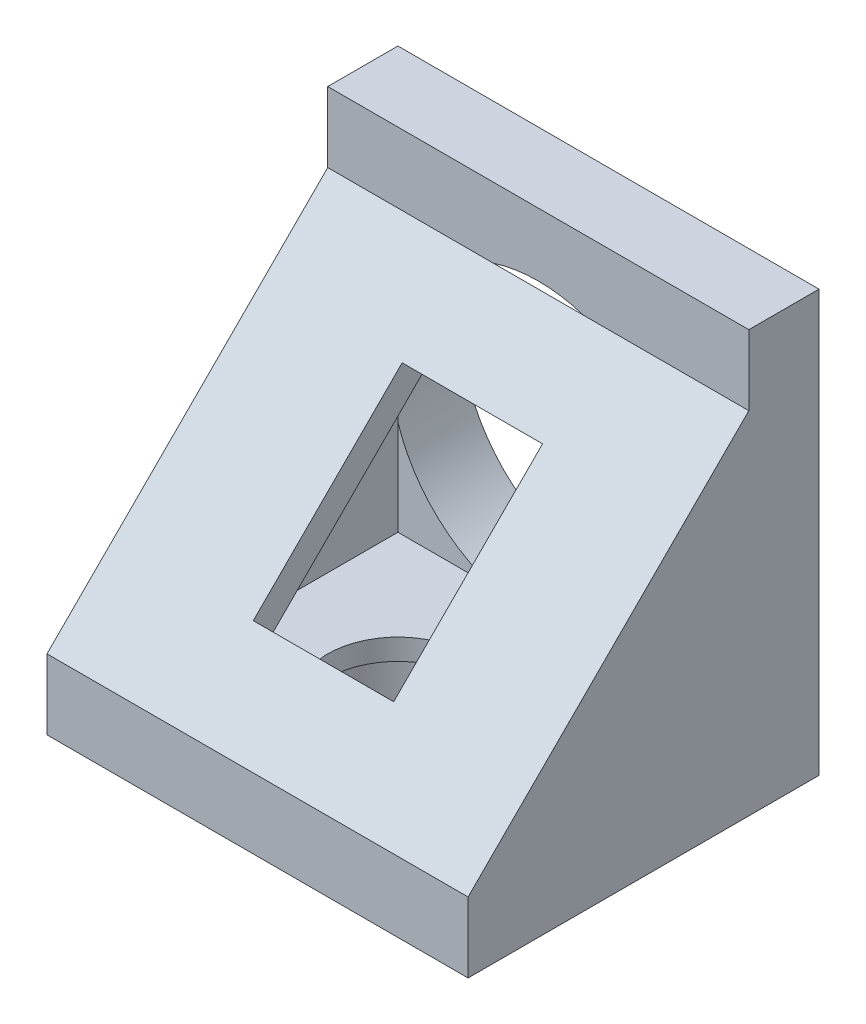
SolidWorks part; units mm, degrees
ref_plane "Front Plane" through (0, 0, 0) normal (1, 0, 0) x (0, 1, 0)
ref_plane "Top Plane" through (0, 0, 0) normal (0, 0, 1) x (0, 1, 0)
ref_plane "Right Plane" through (0, 0, 0) normal (0, 1, 0) x (-1, 0, 0)
sketch "Sketch1" plane through (0, 0, 0) normal (0, 0, 1) x (0, 1, 0)
  line L1 (-15, -15) -> (15, -15)
  line L2 (-15, -15) -> (-15, 15)
  line L3 (-15, 15) -> (15, 15)
  line L4 (15, -15) -> (15, 15)
  line L5 (-15, -15) -> (15, 15) construction
  line L6 (-15, 15) -> (15, -15) construction
  point P0 (0, 0)
  dimension "D1" = 30
  dimension "D2" = 30
extrude "Boss-Extrude1" add sketch "Sketch1" along normal blind 25
sketch "Sketch2" plane through (0, 0, 25) normal (0, 0, 1) x (1, 0, 0)
  line L1 (-10, -10) -> (10, -10)
  line L2 (-10, -10) -> (-10, 10)
  line L3 (-10, 10) -> (10, 10)
  line L4 (10, -10) -> (10, 10)
  line L5 (-10, -10) -> (10, 10) construction
  line L6 (-10, 10) -> (10, -10) construction
  point P0 (0, 0)
  dimension "D1" = 20
  dimension "D2" = 20
extrude "Cut-Extrude1" cut sketch "Sketch2" against normal blind 20
sketch "Sketch3" plane through (15, 0, 0) normal (1, 0, 0) x (0, 1, 0)
  line L0 (-15, 30) -> (15, 0)
  line L1 (15, 0) -> (-15, 0)
  line L2 (15, 0) -> (15, 30)
  line L3 (15, 30) -> (-15, 30)
  line L4 (-15, 0) -> (-15, 30)
  line L5 (-15, 0) -> (-15, 5)
  line L7 (-15, 5) -> (15, 5)
  line L8 (-15, 5) -> (-15, 0)
  line L9 (-15, 0) -> (15, 0)
  line L10 (15, 5) -> (15, 0)
  line M7 (15, 25) -> (-15, 25)
  dimension "D1" = 30
  dimension "D2" = 30
  dimension "D3" = 5
extrude "Cut-Extrude2" cut sketch "Sketch3" against normal blind 43 contours L0 L7 L2 M7
sketch "Sketch4" plane through (0, 7.5, 7.5) normal (0, 0.7071, 0.7071) x (-1, 0, 0)
  line L0 (10, 10.6066) -> (-10, 10.6066) construction
  line L1 (-15, 24.7487) -> (15, 24.7487)
  line L2 (-15, 24.7487) -> (-15, -3.5355)
  line L3 (-15, -3.5355) -> (15, -3.5355)
  line L4 (15, 24.7487) -> (15, -3.5355)
  line L5 (-5, 3.1066) -> (5, 3.1066)
  line L6 (-5, 3.1066) -> (-5, 18.1066)
  line L7 (-5, 18.1066) -> (5, 18.1066)
  line L8 (5, 3.1066) -> (5, 18.1066)
  line L9 (-5, 3.1066) -> (5, 18.1066) construction
  line L10 (-5, 18.1066) -> (5, 3.1066) construction
  point P6 (0, 10.6066)
  dimension "D1" = 10
  dimension "D2" = 15
extrude "Boss-Extrude2" add sketch "Sketch4" against normal blind 2
sketch "Sketch5" plane through (0, 0, 0) normal (0, 0, -1) x (1, 0, 0)
  circle A0 centre (0, 0) radius 10.5
extrude "Cut-Extrude4" cut sketch "Sketch5" against normal blind 5
sketch "Sketch6" plane through (0, -15, 0) normal (0, -1, 0) x (1, 0, 0)
  line L0 (15, 25) -> (15, 0) construction
  line L1 (-15, 25) -> (15, 25)
  line L2 (-15, 25) -> (-15, 5)
  line L3 (-15, 5) -> (15, 5)
  line L4 (15, 25) -> (15, 5)
  circle A0 centre (0, 15) radius 5
  dimension "D1" = 20
extrude "Cut-Extrude6" cut sketch "Sketch6" against normal blind 5 contours A0
sketch "Sketch7" plane through (0, -15, 0) normal (0, -1, 0) x (1, 0, 0)
  circle A0 centre (0, 15) radius 6.5
  circle M1 centre (0, 15) radius 5
extrude "Cut-Extrude7" cut sketch "Sketch7" against normal blind 3.5 contours A0 M1
